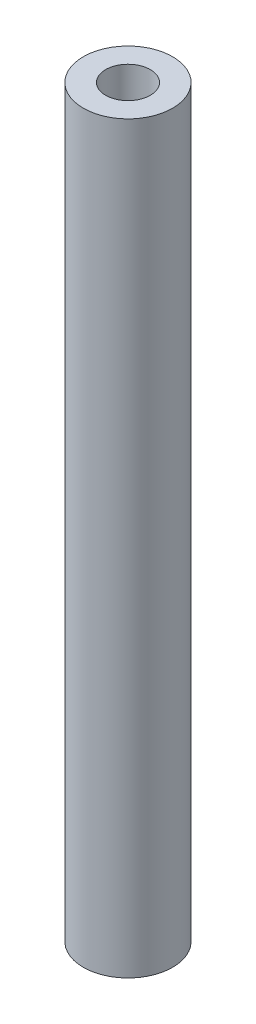
SolidWorks part; units mm, degrees
ref_plane "前视基准面" through (0, 0, 0) normal (0, 0, 1) x (1, 0, 0)
ref_plane "上视基准面" through (0, 0, 0) normal (0, 1, 0) x (1, 0, 0)
ref_plane "右视基准面" through (0, 0, 0) normal (1, 0, 0) x (0, 0, -1)
sketch "草图1" plane through (0, 0, 0) normal (0, 1, 0) x (1, 0, 0)
  circle A0 centre (0, 0) radius 1.5
  circle A1 centre (0, 0) radius 3
  dimension "D1" = 6
  dimension "D2" = 3
extrude "凸台-拉伸1" add sketch "草图1" along normal blind 50
